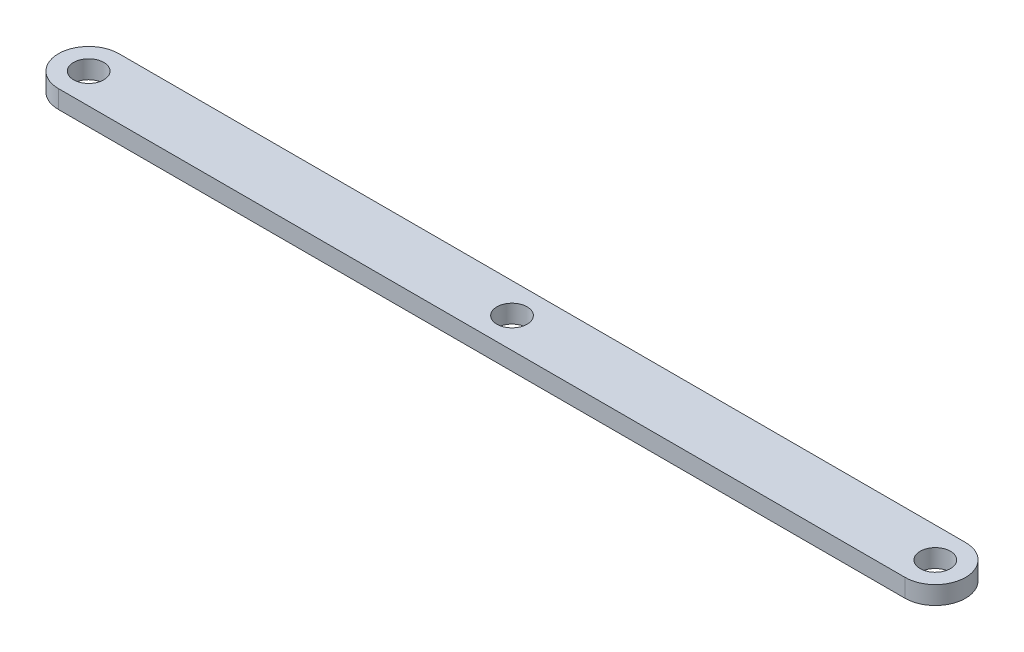
SolidWorks part; units mm, degrees
ref_plane "Front Plane" through (0, 0, 0) normal (0, 0, 1) x (1, 0, 0)
ref_plane "Top Plane" through (0, 0, 0) normal (0, 1, 0) x (1, 0, 0)
ref_plane "Right Plane" through (0, 0, 0) normal (1, 0, 0) x (0, 0, -1)
sketch "Sketch1" plane through (0, 0, 0) normal (0, 1, 0) x (1, 0, 0)
  line L0 (0, 0) -> (140, 0) construction
  line L1 (0, 5) -> (140, 5)
  line L2 (0, -5) -> (140, -5)
  arc A0 (0, 5) -> (0, -5) centre (0, 0) ccw
  arc A1 (140, -5) -> (140, 5) centre (140, 0) ccw
  circle A2 centre (0, 0) radius 2.5
  circle A3 centre (140, 0) radius 2.5
  circle A4 centre (70, 0) radius 2.5
  point P2 (70, 0)
  dimension "D3" = 5
  dimension "D4" = 5
  dimension "D8" = 5
  dimension "D1" = 140
  dimension "D2" = 5
  dimension "D5" = 0
  dimension "D6" = 0
  dimension "D7" = 70
extrude "Boss-Extrude1" add sketch "Sketch1" along normal blind 3
